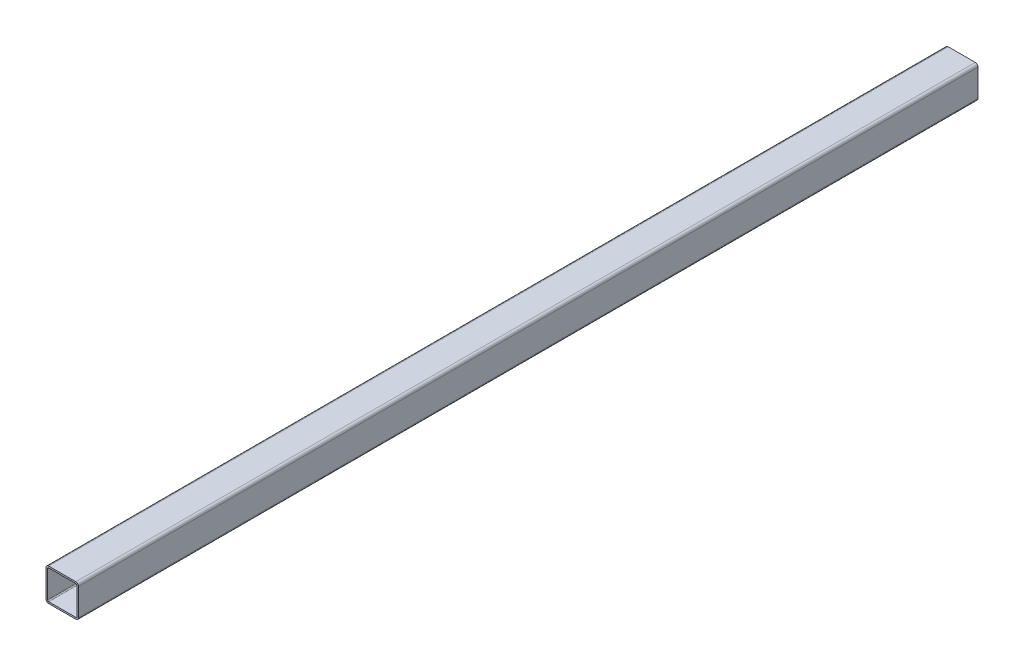
SolidWorks part; units mm, degrees
material "1.0117 (S235J2G4)"
ref_plane "Спереди" through (0, 0, 0) normal (0, 0, 1) x (1, 0, 0)
ref_plane "Сверху" through (0, 0, 0) normal (0, 1, 0) x (1, 0, 0)
ref_plane "Справа" through (0, 0, 0) normal (1, 0, 0) x (0, 0, -1)
sketch "Эскиз1" plane through (0, 0, 0) normal (0, 0, 1) x (1, 0, 0)
  line L0 (25, -6000) -> (-25, -6000) construction
  point P4 (0, -6000)
  point P11 (30, 30)
  point P18 (30, -30)
  line B0 (-25, -30) -> (25, -30)
  line B1 (-30, -25) -> (-30, 25)
  line B2 (-25, 30) -> (25, 30)
  line B3 (30, -25) -> (30, 25)
  line B4 (30, 0) -> (-30, 0) construction
  arc B5 (25, 30) -> (30, 25) centre (25, 25) cw
  arc B6 (-30, 25) -> (-25, 30) centre (-25, 25) cw
  arc B7 (-25, -30) -> (-30, -25) centre (-25, -25) cw
  arc B8 (25, -30) -> (30, -25) centre (25, -25) ccw
  dimension "D1" = 60
sketch_block_instance "Блок1-1"
sketch_block "Блок1" parameters "D1"=5
extrude "Бобышка-Вытянуть1" add sketch "Эскиз1" along normal mid plane 1660
shell "Оболочка1" thickness 3
sketch "Эскиз3" plane through (0, 0, 0) normal (0, 1, 0) x (1, 0, 0)
  line L0 (0, 0) -> (0, -830) construction
  line L1 (25, -830) -> (-25, -830) construction
  line L2 (0, 0) -> (0, 30) construction
  line L3 (0, -830) -> (0, -860) construction
  dimension "D1" = 30
  dimension "D2" = 30
sketch "Эскиз4" plane through (0, 30, 0) normal (0, 1, 0) x (1, 0, 0)
  line L0 (0, -830) -> (0, 830) construction
  line L1 (25, -830) -> (-25, -830) construction
  line L2 (25, 830) -> (-25, 830) construction
sketch "Эскиз5" plane through (0, -30, 0) normal (0, -1, 0) x (-1, 0, 0)
  line L0 (0, -862.0825) -> (0, 830) construction
  line L1 (25, 830) -> (-25, 830) construction
  line L2 (-25, 0) -> (0, 0) construction
  line L3 (-25, -830) -> (-25, 830) construction
